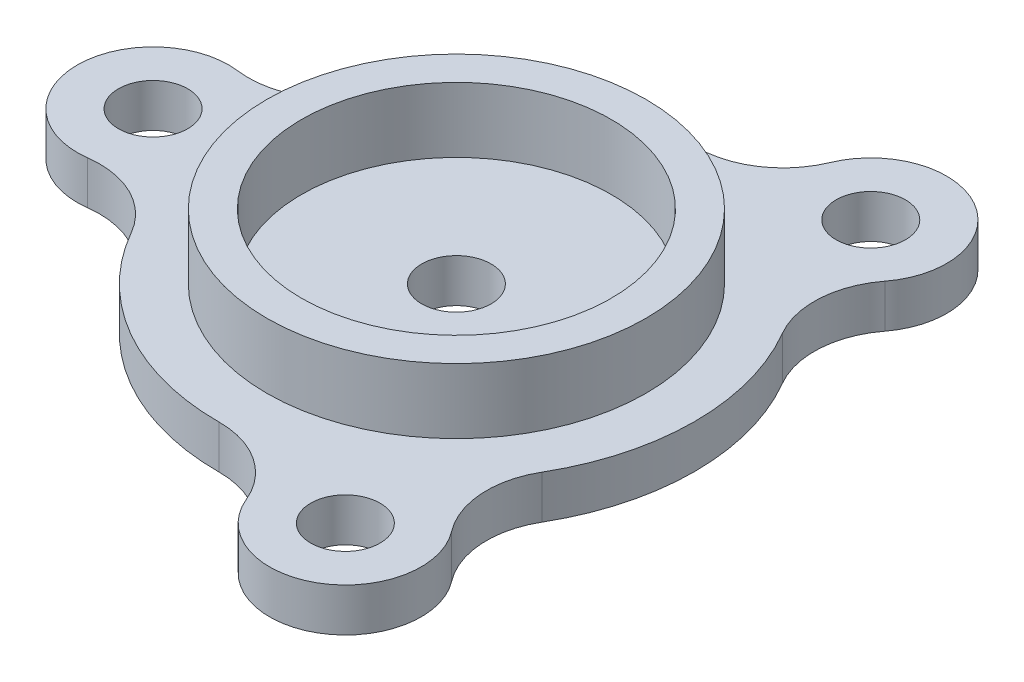
SolidWorks part; units mm, degrees
ref_plane "前视基准面" through (0, 0, 0) normal (0, 0, 1) x (1, 0, 0)
ref_plane "上视基准面" through (0, 0, 0) normal (0, 1, 0) x (1, 0, 0)
ref_plane "右视基准面" through (0, 0, 0) normal (1, 0, 0) x (0, 0, -1)
sketch "草图1" plane through (0, 0, 0) normal (0, 1, 0) x (1, 0, 0)
  circle A0 centre (0, 0) radius 11
  dimension "D1" = 22
extrude "凸台-拉伸1" add sketch "草图1" along normal blind 2
sketch "草图2" plane through (0, 2, 0) normal (0, 1, 0) x (1, 0, 0)
  circle A0 centre (7, 12.1244) radius 1.6 construction
  circle A1 centre (7, -12.1244) radius 1.6 construction
  circle A2 centre (-14, 0) radius 1.6 construction
  circle A3 centre (7, 12.1244) radius 1.6
  circle A4 centre (7, -12.1244) radius 1.6
  circle A5 centre (-14, 0) radius 1.6
  arc A13 (11, 0) -> (9.4994, 5.5464) centre (0, 0) ccw
  arc A14 (9.4994, -5.5464) -> (11, 0) centre (0, 0) ccw
  arc A15 (9.4994, -5.5464) -> (9.7784, -9.9958) centre (12.9537, -7.5632) ccw
  arc A16 (3.7675, -13.4662) -> (9.7784, -9.9958) centre (7, -12.1244) ccw
  arc A17 (0.0536, -10.9999) -> (9.4994, -5.5464) centre (0, 0) ccw
  arc A18 (-9.553, -5.4535) -> (0.0536, -10.9999) centre (0, 0) ccw
  arc A19 (-9.553, -5.4535) -> (-13.5458, -3.4704) centre (-13.0268, -7.4366) ccw
  arc A20 (-13.5458, 3.4704) -> (-13.5458, -3.4704) centre (-14, 0) ccw
  arc A21 (-13.5458, 3.4704) -> (-9.553, 5.4535) centre (-13.0268, 7.4366) ccw
  arc A22 (0.0536, 10.9999) -> (-9.553, 5.4535) centre (0, 0) ccw
  arc A23 (9.4994, 5.5464) -> (0.0536, 10.9999) centre (0, 0) ccw
  arc A24 (9.7784, 9.9958) -> (3.7675, 13.4662) centre (7, 12.1244) ccw
  arc A25 (9.7784, 9.9958) -> (9.4994, 5.5464) centre (12.9537, 7.5632) ccw
  arc A28 (9.4994, -5.5464) -> (9.7784, -9.9958) centre (12.9537, -7.5632) ccw
  arc A29 (3.7675, -13.4662) -> (9.7784, -9.9958) centre (7, -12.1244) ccw
  arc A32 (-9.553, -5.4535) -> (-13.5458, -3.4704) centre (-13.0268, -7.4366) ccw
  arc A33 (-13.5458, 3.4704) -> (-13.5458, -3.4704) centre (-14, 0) ccw
  arc A34 (-13.5458, 3.4704) -> (-9.553, 5.4535) centre (-13.0268, 7.4366) ccw
  arc A37 (9.7784, 9.9958) -> (3.7675, 13.4662) centre (7, 12.1244) ccw
  arc A38 (9.7784, 9.9958) -> (9.4994, 5.5464) centre (12.9537, 7.5632) ccw
  arc A58 (-9.553, 5.4535) -> (-9.553, -5.4535) centre (0, 0) ccw
  arc A69 (3.7675, -13.4662) -> (0.0536, -10.9999) centre (0.0731, -14.9998) ccw
  arc A70 (3.7675, -13.4662) -> (0.0536, -10.9999) centre (0.0731, -14.9998) ccw
  arc A71 (0.0536, 10.9999) -> (3.7675, 13.4662) centre (0.0731, 14.9998) ccw
  arc A72 (0.0536, 10.9999) -> (3.7675, 13.4662) centre (0.0731, 14.9998) ccw
  dimension "D1" = 0
extrude "凸台-拉伸2" add sketch "草图2" against normal up to surface (2 mm away) up to face at (0, 0, 11)
sketch "草图3" plane through (0, 2, 0) normal (0, 1, 0) x (1, 0, 0)
  circle A0 centre (0, 0) radius 1.6
  dimension "D1" = 3.2
extrude "切除-拉伸1" cut sketch "草图3" against normal up to next
sketch "草图4" plane through (0, 2, 0) normal (0, 1, 0) x (1, 0, 0)
  circle A0 centre (0, 0) radius 7.15
  circle A1 centre (0, 0) radius 8.75
  dimension "D1" = 14.3
  dimension "D2" = 17.5
extrude "凸台-拉伸3" add sketch "草图4" along normal blind 3
